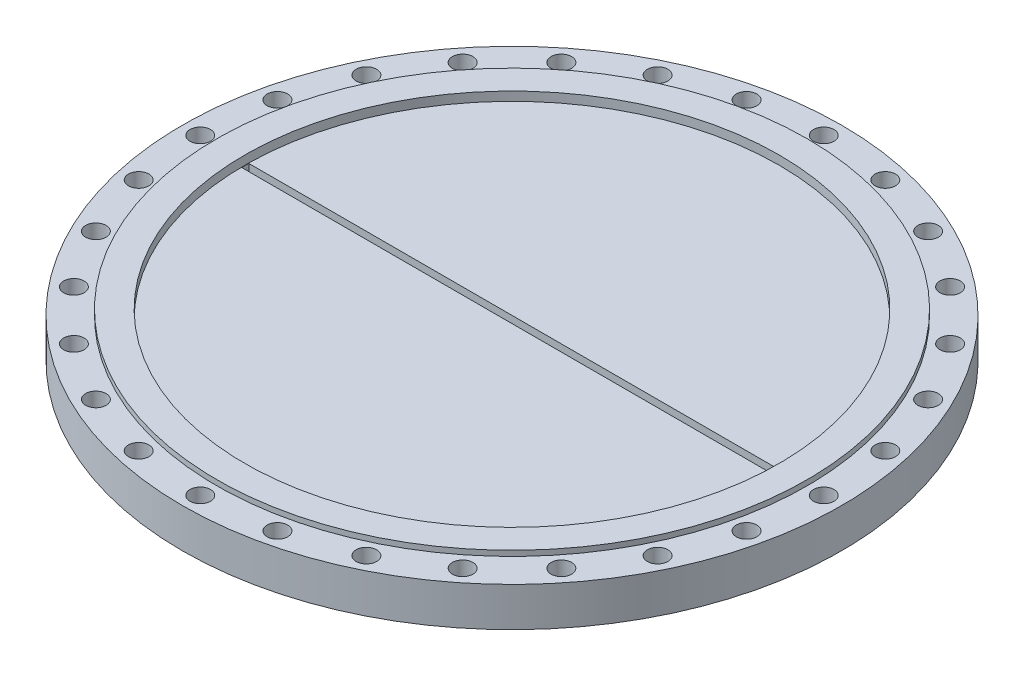
SolidWorks part; units mm, degrees
material " 12Х18Н10Т ГОСТ 4543-71"
ref_plane "Спереди" through (0, 0, 0) normal (0, 0, 1) x (1, 0, 0)
ref_plane "Сверху" through (0, 0, 0) normal (0, 1, 0) x (1, 0, 0)
ref_plane "Справа" through (0, 0, 0) normal (1, 0, 0) x (0, 0, -1)
sketch "Эскиз1" plane through (0, 0, 0) normal (0, 0, 1) x (1, 0, 0)
  line L0 (0, 0) -> (0, 152.1529) construction
  line L2 (-300, 50) -> (-331.5, 50)
  line L3 (-331.5, 50) -> (-331.5, 44)
  line L5 (0, 0) -> (0, 40)
  line L6 (-331.5, 44) -> (-370, 44)
  line L7 (-370, 44) -> (-370, 0)
  line L8 (-370, 0) -> (0, 0)
  line L11 (0, 40) -> (-300, 40)
  line L12 (-300, 40) -> (-300, 50)
  point P15 (-317, 30)
  dimension "D1" = 740
  dimension "D2" = 40
  dimension "D4" = 634
  dimension "D5" = 663
  dimension "D6" = 6
  dimension "D7" = 50
  dimension "D9" = 10
  dimension "D10" = 600
revolve "Повернуть1" add sketch "Эскиз1" angle 360 about L0
sketch "Эскиз2" plane through (0, 44, 0) normal (0, 1, 0) x (1, 0, 0)
  circle A0 centre (0, 0) radius 350 construction
  circle A1 centre (0, 350) radius 11.5
  circle A2 centre (77.8823, 341.2248) radius 11.5
  circle A3 centre (151.8593, 315.3391) radius 11.5
  circle A4 centre (218.2214, 273.641) radius 11.5
  circle A5 centre (273.641, 218.2214) radius 11.5
  circle A6 centre (315.3391, 151.8593) radius 11.5
  circle A7 centre (341.2248, 77.8823) radius 11.5
  circle A8 centre (350, 0) radius 11.5
  circle A9 centre (341.2248, -77.8823) radius 11.5
  circle A10 centre (315.3391, -151.8593) radius 11.5
  circle A11 centre (273.641, -218.2214) radius 11.5
  circle A12 centre (218.2214, -273.641) radius 11.5
  circle A13 centre (151.8593, -315.3391) radius 11.5
  circle A14 centre (77.8823, -341.2248) radius 11.5
  circle A15 centre (0, -350) radius 11.5
  circle A16 centre (-77.8823, -341.2248) radius 11.5
  circle A17 centre (-151.8593, -315.3391) radius 11.5
  circle A18 centre (-218.2214, -273.641) radius 11.5
  circle A19 centre (-273.641, -218.2214) radius 11.5
  circle A20 centre (-315.3391, -151.8593) radius 11.5
  circle A21 centre (-341.2248, -77.8823) radius 11.5
  circle A22 centre (-350, 0) radius 11.5
  circle A23 centre (-341.2248, 77.8823) radius 11.5
  circle A24 centre (-315.3391, 151.8593) radius 11.5
  circle A25 centre (-273.641, 218.2214) radius 11.5
  circle A26 centre (-218.2214, 273.641) radius 11.5
  circle A27 centre (-151.8593, 315.3391) radius 11.5
  circle A28 centre (-77.8823, 341.2248) radius 11.5
  point P61 (0, 0)
  dimension "D1" = 700
  dimension "D2" = 23
  dimension "D3" = 28
extrude "Вырез-Вытянуть1" cut sketch "Эскиз2" against normal through all
sketch "Эскиз3" plane through (0, 40, 0) normal (0, 1, 0) x (1, 0, 0)
  line L1 (-299.5, 4) -> (299.5, 4)
  line L2 (-299.5, 4) -> (-299.5, -4)
  line L3 (-299.5, -4) -> (299.5, -4)
  line L4 (299.5, 4) -> (299.5, -4)
  line L5 (-299.5, 4) -> (299.5, -4) construction
  line L6 (-299.5, -4) -> (299.5, 4) construction
  point P0 (0, 0)
  dimension "D1" = 599
  dimension "D2" = 8
extrude "Вырез-Вытянуть2" cut sketch "Эскиз3" against normal blind 10
